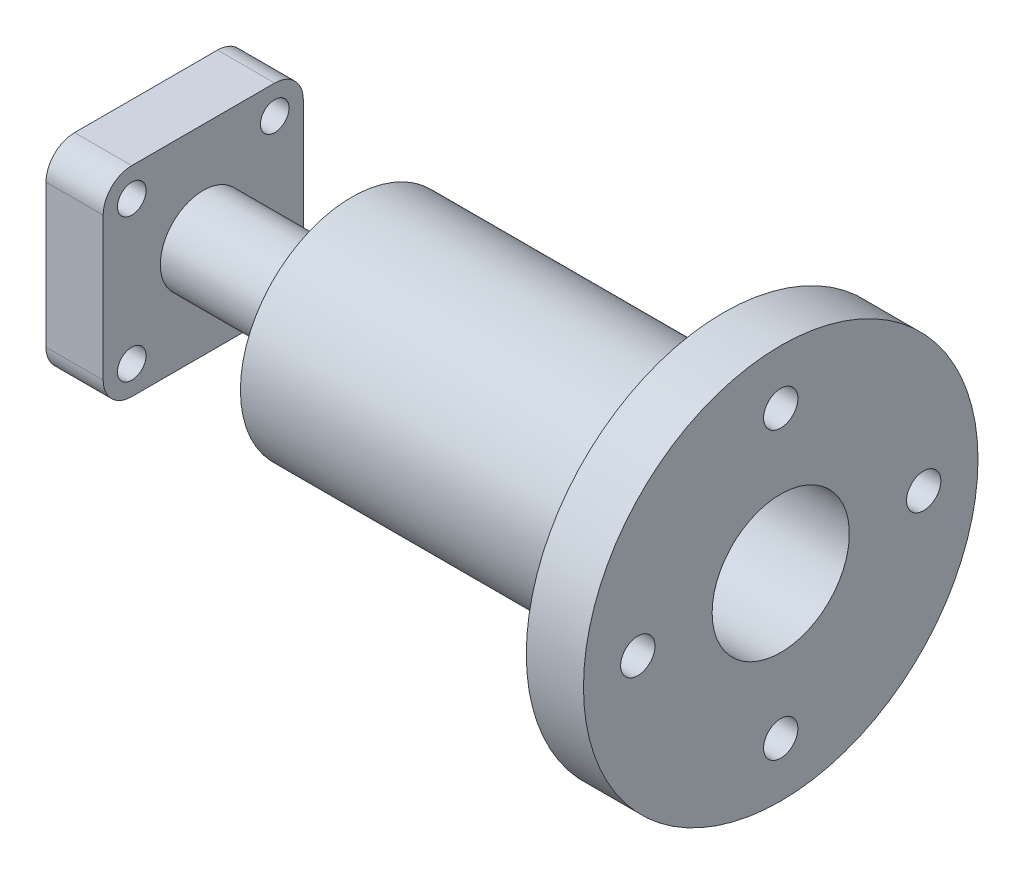
SolidWorks part; units mm, degrees
ref_plane "Front Plane" through (0, 0, 0) normal (0, 0, 1) x (1, 0, 0)
ref_plane "Top Plane" through (0, 0, 0) normal (0, 1, 0) x (1, 0, 0)
ref_plane "Right Plane" through (0, 0, 0) normal (1, 0, 0) x (0, 0, -1)
sketch "Sketch1" plane through (0, 0, 0) normal (0, 1, 0) x (1, 0, 0)
  line L12 (0, 15) -> (52, 15)
  line L13 (52, 15) -> (52, 39)
  line L14 (52, 39) -> (182, 39)
  line L15 (182, 39) -> (182, 69)
  line L16 (182, 69) -> (202, 69)
  line L17 (202, 69) -> (202, 24)
  line L18 (202, 24) -> (58, 24)
  line L19 (58, 24) -> (58, 9)
  line L20 (58, 9) -> (0, 9)
  line L21 (0, 9) -> (0, 15)
  line L22 (0, 0) -> (142.5211, 0) construction
  dimension "D1" = 15
  dimension "D2" = 30
  dimension "D3" = 60
  dimension "D4" = 20
  dimension "D5" = 202
  dimension "D6" = 130
  dimension "D7" = 9
  dimension "D8" = 24
  dimension "D9" = 6
revolve "Revolve1" add sketch "Sketch1" angle 360 about L22
sketch "Sketch2" plane through (0, 0, 0) normal (-1, 0, 0) x (0, 0, 1)
  line L1 (-35, 35) -> (35, 35)
  line L2 (-35, 35) -> (-35, -35)
  line L3 (-35, -35) -> (35, -35)
  line L4 (35, 35) -> (35, -35)
  line L5 (-35, 35) -> (35, -35) construction
  line L6 (-35, -35) -> (35, 35) construction
  point P0 (0, 0)
  dimension "D1" = 70
  dimension "D2" = 70
extrude "Boss-Extrude1" add sketch "Sketch2" along normal blind 20
fillet "Fillet1" radius 10 4 edges at (-10, 35, -35) (-10, 35, 35) (-10, -35, -35) (-10, -35, 35)
hole_wizard "Hole1" positions "Sketch3" profile "Sketch4" legacy
sketch "Sketch3" plane through (-20, 0, 0) normal (-1, 0, 0) x (0, 0, 1)
  point P0 (25, 25)
  point P3 (25, -25)
  point P6 (-25, -25)
  point P9 (-25, 25)
sketch "Sketch4" plane through (-20, 25, 25) normal (0, 1, 0) x (0, 0, 1)
  line L0 (0, 0) -> (0, 20)
  line L1 (0, 20) -> (5, 20)
  line L2 (5, 20) -> (5, 0)
  line L3 (5, 0) -> (0, 0)
  line L4 (0, 110) -> (0, -10) construction
  dimension "Diameter" = 10
  dimension "Depth" = 20
hole_wizard "Hole2" positions "Sketch5" profile "Sketch6" legacy end condition up to next
sketch "Sketch5" plane through (182, 0, 0) normal (-1, 0, 0) x (0, 0, 1)
  point P0 (50, 0)
  point P6 (0, 0)
  dimension "D1" = 50
sketch "Sketch6" plane through (182, 0, 50) normal (0, 1, 0) x (0, 0, 1)
  line L0 (0, 0) -> (0, 20)
  line L1 (0, 20) -> (6, 20)
  line L2 (6, 20) -> (6, 0)
  line L3 (6, 0) -> (0, 0)
  line L4 (0, 110) -> (0, -10) construction
  dimension "Diameter" = 12
  dimension "Depth" = 20
pattern_circular "CirPattern1" count 4 over 360 about axis through (0, 0, 0) along (1, 0, 0) of "Hole2"
